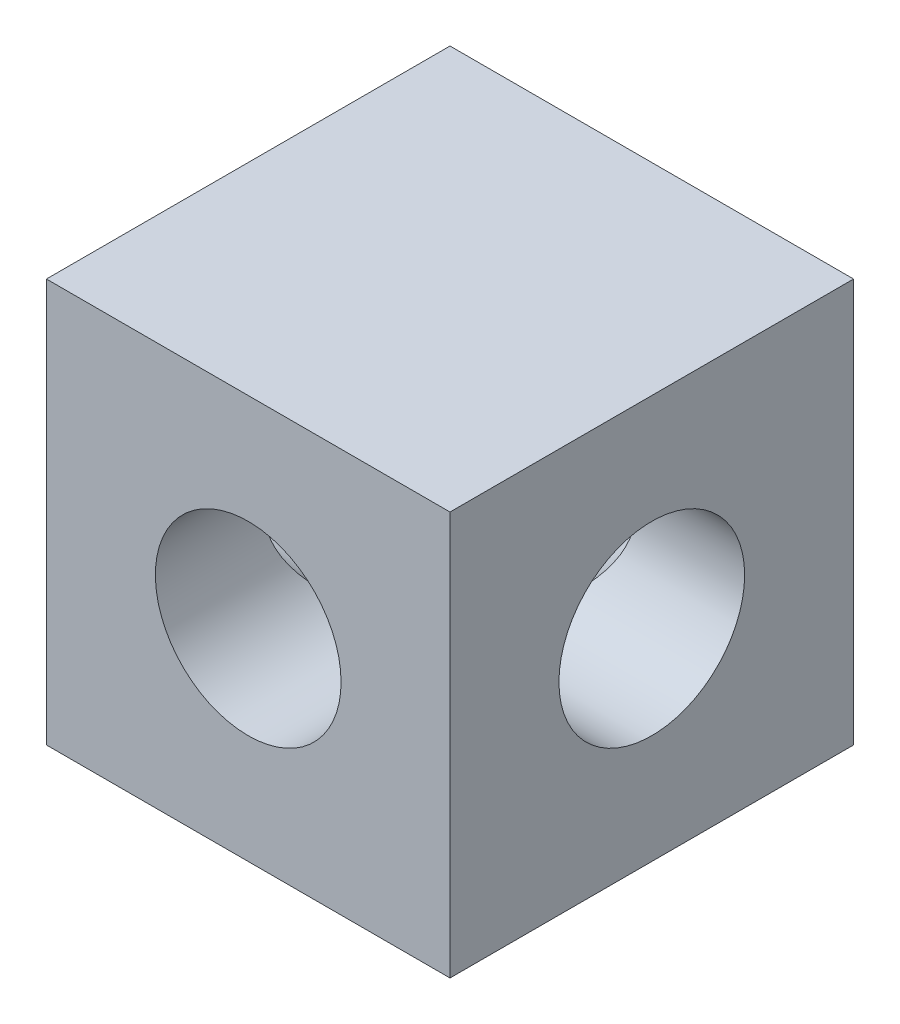
SolidWorks part; units mm, degrees
ref_plane "Front Plane" through (0, 0, 0) normal (0, 0, 1) x (1, 0, 0)
ref_plane "Top Plane" through (0, 0, 0) normal (0, 1, 0) x (1, 0, 0)
ref_plane "Right Plane" through (0, 0, 0) normal (1, 0, 0) x (0, 0, -1)
sketch "Sketch1" plane through (0, 0, 0) normal (0, 0, 1) x (1, 0, 0)
  line L1 (10.16, -10.16) -> (-10.16, -10.16)
  line L2 (10.16, -10.16) -> (10.16, 10.16)
  line L3 (10.16, 10.16) -> (-10.16, 10.16)
  line L4 (-10.16, -10.16) -> (-10.16, 10.16)
  line L5 (10.16, -10.16) -> (-10.16, 10.16) construction
  line L6 (10.16, 10.16) -> (-10.16, -10.16) construction
  circle A0 centre (0, 0) radius 4.675
  point P0 (0, 0)
  dimension "D2" = 9.35
  dimension "D1" = 20.32
extrude "Boss-Extrude1" add sketch "Sketch1" along normal blind 20.32
sketch "Sketch2" plane through (10.16, 0, 0) normal (1, 0, 0) x (0, 0, -1)
  line L0 (-20.32, -10.16) -> (0, -10.16) construction
  circle A0 centre (-10.16, 0) radius 4.675
  point P2 (0, 0)
  point P4 (0, 0)
  point P5 (0, 0)
  point P8 (-10.16, -10.16)
  dimension "D1" = 9.35
extrude "Cut-Extrude1" cut sketch "Sketch2" against normal through all
